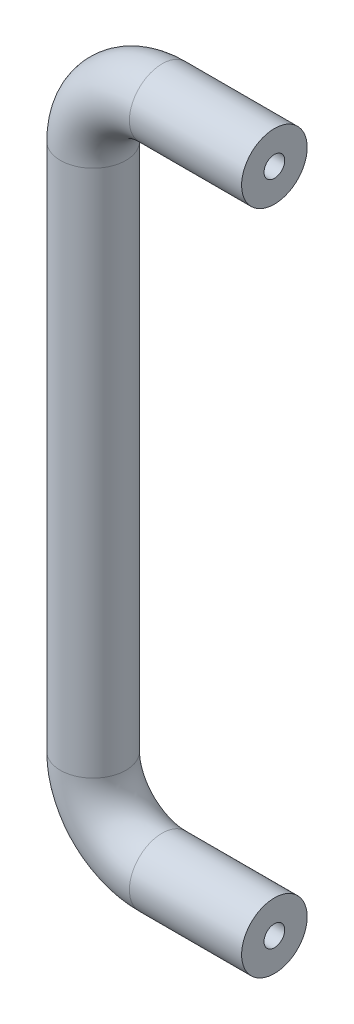
SolidWorks part; units mm, degrees
ref_plane "Front Plane" through (0, 0, 0) normal (0, 0, 1) x (1, 0, 0)
ref_plane "Top Plane" through (0, 0, 0) normal (0, 1, 0) x (1, 0, 0)
ref_plane "Right Plane" through (0, 0, 0) normal (1, 0, 0) x (0, 0, -1)
sketch "Esboço1" plane through (0, 0, 0) normal (0, 0, 1) x (1, 0, 0)
  line L0 (0, 0) -> (-16.25, 0)
  line L1 (-26.25, -10) -> (-26.25, -86.5)
  line L2 (-16.25, -96.5) -> (0, -96.5)
  arc A0 (-26.25, -86.5) -> (-16.25, -96.5) centre (-16.25, -86.5) ccw
  arc A1 (-16.25, 0) -> (-26.25, -10) centre (-16.25, -10) ccw
  point P7 (-26.25, -96.5)
  point P10 (-26.25, 0)
  dimension "D3" = 10
  dimension "D1" = 26.25
  dimension "D2" = 96.5
sketch "Esboço2" plane through (0, 0, 0) normal (1, 0, 0) x (0, 0, -1)
  circle A0 centre (0, 0) radius 4.75
  dimension "D1" = 9.5
sweep "Varredura1" add profiles "Esboço2" path "Esboço1"
sketch "Esboço3" plane through (0, 0, 0) normal (1, 0, 0) x (0, 0, -1)
  circle A0 centre (0, 0) radius 1.5
  circle A1 centre (0, -96.5) radius 1.5
  dimension "D1" = 3
extrude "Corte-extrusão1" cut sketch "Esboço3" against normal blind 10
